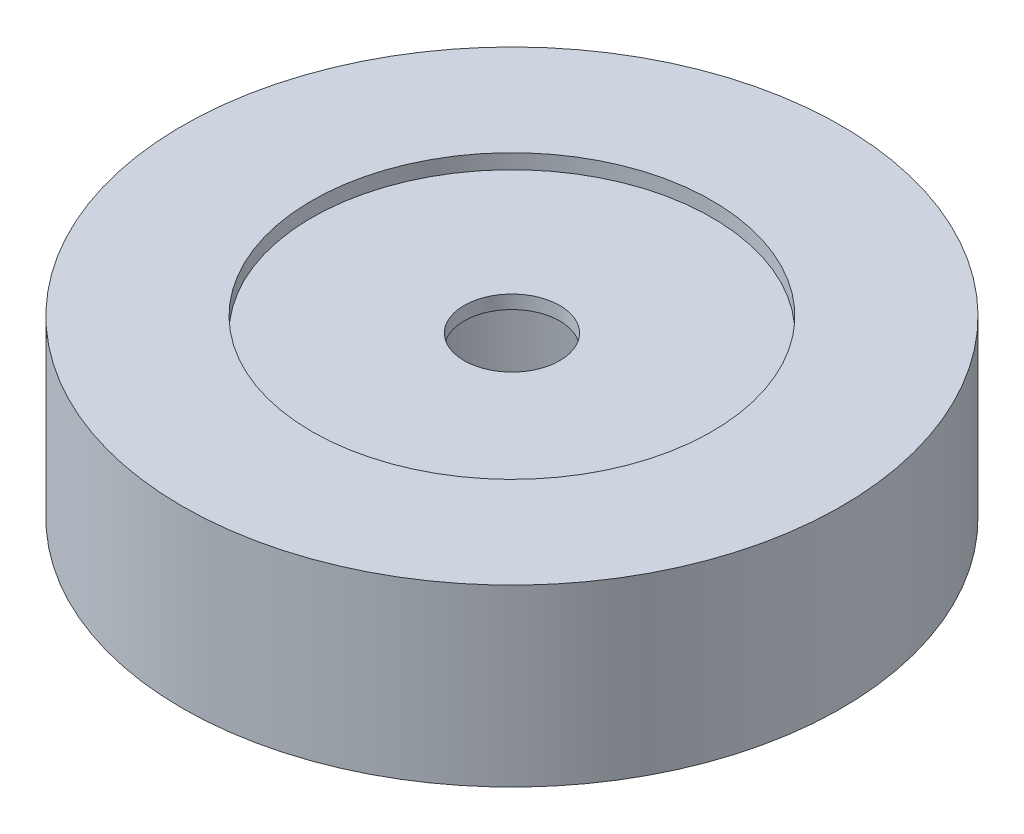
SolidWorks part; units mm, degrees
ref_plane "Front Plane" through (0, 0, 0) normal (0, 0, 1) x (1, 0, 0)
ref_plane "Top Plane" through (0, 0, 0) normal (0, 1, 0) x (1, 0, 0)
ref_plane "Right Plane" through (0, 0, 0) normal (1, 0, 0) x (0, 0, -1)
sketch "Sketch1" plane through (0, 0, 0) normal (0, 1, 0) x (1, 0, 0)
  circle A0 centre (0, 0) radius 227.33
  circle A1 centre (0, 0) radius 33
  dimension "D1" = 454.66
  dimension "D2" = 66
extrude "Boss-Extrude1" add sketch "Sketch1" along normal blind 120.65
sketch "Sketch2" plane through (0, 0, 0) normal (0, -1, 0) x (1, 0, 0)
  circle A0 centre (0, 0) radius 120.5
  dimension "D1" = 241
extrude "Cut-Extrude1" cut sketch "Sketch2" against normal blind 101.22
sketch "Sketch3" plane through (0, 120.65, 0) normal (0, 1, 0) x (1, 0, 0)
  circle A0 centre (0, 0) radius 138
  dimension "D1" = 276
extrude "Cut-Extrude2" cut sketch "Sketch3" against normal blind 10.16
